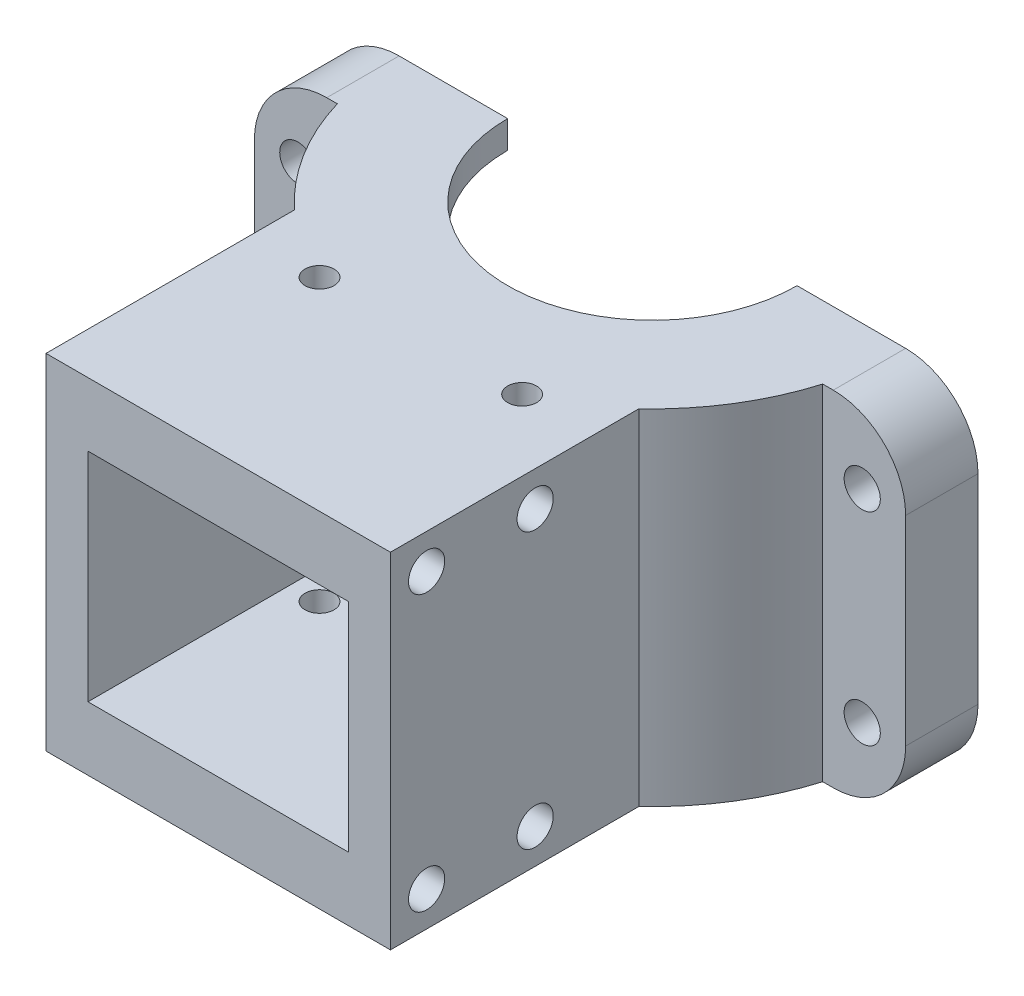
SolidWorks part; units mm, degrees
ref_plane "Alzado" through (0, 0, 0) normal (0, 0, 1) x (1, 0, 0)
ref_plane "Planta" through (0, 0, 0) normal (0, 1, 0) x (1, 0, 0)
ref_plane "Vista lateral" through (0, 0, 0) normal (1, 0, 0) x (0, 0, -1)
sketch "Croquis1" plane through (0, 0, 0) normal (0, 0, 1) x (1, 0, 0)
  line L1 (-23.8, 23.8) -> (23.8, 23.8)
  line L2 (-23.8, 23.8) -> (-23.8, -23.8)
  line L3 (-23.8, -23.8) -> (23.8, -23.8)
  line L4 (23.8, 23.8) -> (23.8, -23.8)
  line L5 (-23.8, 23.8) -> (23.8, -23.8) construction
  line L6 (-23.8, -23.8) -> (23.8, 23.8) construction
  point P0 (0, 0)
  dimension "D1" = 47.6
  dimension "D2" = 47.6
extrude "Saliente-Extruir1" add sketch "Croquis1" along normal blind 40
sketch "Croquis3" plane through (0, 23.8, 0) normal (0, 1, 0) x (1, 0, 0)
  line L0 (0, 0) -> (0, 32.7983) construction
  line L1 (23.8, 0) -> (-23.8, 0) construction
  circle A0 centre (0, 20) radius 27.5 construction
  circle A1 centre (0, 20) radius 35
  dimension "D1" = 55
  dimension "D3" = 70
  dimension "D2" = 20
extrude "Saliente-Extruir2" add sketch "Croquis3" against normal blind 47.6 contours A1
sketch "Croquis4" plane through (0, 23.8, 0) normal (0, 1, 0) x (1, 0, 0)
  line L1 (-39.3986, 20) -> (40.6014, 20)
  line L2 (-39.3986, 20) -> (-39.3986, 60)
  line L3 (-39.3986, 60) -> (40.6014, 60)
  line L4 (40.6014, 20) -> (40.6014, 60)
  dimension "D1" = 20
  dimension "D2" = 80
  dimension "D3" = 40
extrude "Cortar-Extruir1" cut sketch "Croquis4" against normal through all
sketch "Croquis9" plane through (0, -23.8, 0) normal (0, -1, 0) x (1, 0, 0)
  line L1 (-45, -20) -> (45, -20)
  line L2 (-45, -20) -> (-45, -10)
  line L3 (-45, -10) -> (45, -10)
  line L4 (45, -20) -> (45, -10)
  dimension "D1" = 10
  dimension "D2" = 10
  dimension "D3" = 10
extrude "Saliente-Extruir3" add sketch "Croquis9" against normal blind 47.6
sketch "Croquis5" plane through (0, 23.8, 0) normal (0, 1, 0) x (1, 0, 0)
  line L0 (-45, 20) -> (45, 20) construction
  circle A0 centre (0, 20) radius 27.5
  dimension "D1" = 55
extrude "Cortar-Extruir2" cut sketch "Croquis5" against normal blind 37 from offset 3.8 offset against normal yes
sketch "Croquis6" plane through (0, 0, 40) normal (0, 0, 1) x (1, 0, 0)
  line L1 (18, 15) -> (-18, 15)
  line L2 (18, 15) -> (18, -15)
  line L3 (18, -15) -> (-18, -15)
  line L4 (-18, 15) -> (-18, -15)
  line L5 (18, 15) -> (-18, -15) construction
  line L6 (18, -15) -> (-18, 15) construction
  point P0 (0, 0)
  dimension "D1" = 30
  dimension "D2" = 36
extrude "Cortar-Extruir3" cut sketch "Croquis6" against normal through all
sketch "Croquis7" plane through (0, 20, 0) normal (0, -1, 0) x (1, 0, 0)
  line L0 (27.5, -20) -> (-27.5, -20) construction
  circle A0 centre (0, -20) radius 30
  dimension "D1" = 60
extrude "Cortar-Extruir4" cut sketch "Croquis7" along normal blind 17 from offset 10
sketch "Croquis8" plane through (23.8, 0, 0) normal (1, 0, 0) x (0, 0, -1)
  line L0 (-40, 19) -> (-5.6624, 19) construction
  line L1 (-40, -23.8) -> (-40, 23.8) construction
  line L2 (-5.6624, -23.8) -> (-5.6624, 23.8) construction
  line L3 (-40, -19) -> (-5.6624, -19) construction
  circle A0 centre (-35, 19) radius 2.5
  circle A1 centre (-20, 19) radius 2.5
  circle A2 centre (-20, -19) radius 2.5
  circle A3 centre (-35, -19) radius 2.5
  dimension "D3" = 5
  dimension "D4" = 5
  dimension "D5" = 5
  dimension "D6" = 5
  dimension "D7" = 5
  dimension "D8" = 15
  dimension "D9" = 15
  dimension "D10" = 5
  dimension "D1" = 4.8
  dimension "D2" = 4.8
extrude "Cortar-Extruir5" cut sketch "Croquis8" against normal through all
sketch "Croquis11" plane through (0, 0, -20) normal (0, 0, -1) x (-1, 0, 0)
  line L0 (45, 23.8) -> (45, -23.8) construction
  line L1 (45, 23.8) -> (-45, 23.8) construction
  line L2 (0, 0) -> (45, 0) construction
  line L3 (0, 0) -> (0, 23.8) construction
  circle A0 centre (39, 14) radius 2.5
  circle A1 centre (39, -14) radius 2.5
  circle A2 centre (-39, -14) radius 2.5
  circle A3 centre (-39, 14) radius 2.5
  dimension "D1" = 5
  dimension "D2" = 6
  dimension "D3" = 9.8
extrude "Cortar-Extruir7" cut sketch "Croquis11" against normal through all
fillet "Redondeo1" radius 10 4 edges at (-45, -23.8, -15) (-45, 23.8, -15) (45, -23.8, -15) (45, 23.8, -15)
sketch "Croquis10" plane through (0, 23.8, 0) normal (0, 1, 0) x (1, 0, 0)
  line L0 (-35, 20) -> (35, 20) construction
  circle A0 centre (0, 20) radius 20
  dimension "D1" = 40
extrude "Cortar-Extruir6" cut sketch "Croquis10" against normal through all
sketch "Croquis13" plane through (0, 23.8, 0) normal (0, 1, 0) x (1, 0, 0)
  line L1 (-35, 20) -> (-45, 20) construction
  line L2 (45, 20) -> (35, 20) construction
  circle A0 centre (-14, -12) radius 2
  circle A1 centre (14, -12) radius 2
  dimension "D1" = 4
  dimension "D2" = 4
  dimension "D5" = 32
  dimension "D6" = 32
extrude "Cortar-Extruir8" cut sketch "Croquis13" against normal through all
sketch "Croquis14" plane through (0, -23.8, 0) normal (0, -1, 0) x (1, 0, 0)
  line L0 (0, -20) -> (0, 40) construction
  line L1 (-23.8, 40) -> (23.8, 40) construction
  line L2 (0, -20) -> (-32.5412, 12.5412) construction
  line L3 (0, -20) -> (31.9749, 11.9749) construction
  circle A0 centre (-18.7383, -1.2617) radius 6
  circle A1 centre (18.7383, -1.2617) radius 6
  dimension "D2" = 12
  dimension "D3" = 12
  dimension "D4" = 26.5
  dimension "D5" = 26.5
  dimension "D1" = 45
extrude "Saliente-Extruir4" add sketch "Croquis14" along normal blind 1.2
sketch "Croquis15" plane through (0, -25, 0) normal (0, -1, 0) x (1, 0, 0)
  circle A0 centre (18.7383, -1.2617) radius 1.5
  circle A1 centre (-18.7383, -1.2617) radius 1.5
  dimension "D1" = 3
  dimension "D2" = 3
extrude "Cortar-Extruir9" cut sketch "Croquis15" against normal blind 8
